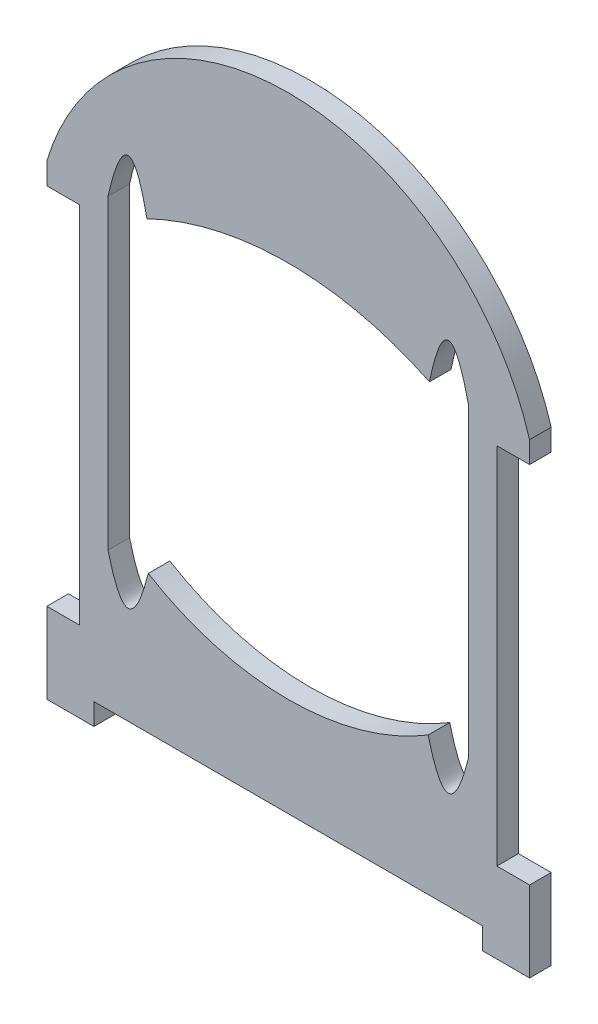
SolidWorks part; units mm, degrees
ref_plane "Front Plane" through (0, 0, 0) normal (0, 0, 1) x (1, 0, 0)
ref_plane "Top Plane" through (0, 0, 0) normal (0, 1, 0) x (1, 0, 0)
ref_plane "Right Plane" through (0, 0, 0) normal (1, 0, 0) x (0, 0, -1)
sketch "Sketch1" plane through (0, 0, 0) normal (0, 0, 1) x (1, 0, 0)
  line L0 (-31.0002, 89.8) -> (31.0002, 89.8) construction
  line L1 (-19.45, 0) -> (-19.45, 22.2)
  line L2 (-19.45, 22.2) -> (19.45, 22.2) construction
  line L3 (19.45, 3) -> (19.45, 22.2)
  line L4 (19.45, 22.2) -> (25.05, 22.2) construction
  line L5 (22.25, 22.2) -> (22.25, 16.6) construction
  line L6 (25.05, 22.2) -> (25.05, 71.1)
  line L7 (29, 72.2) -> (29, -3)
  line L8 (22.25, 16.6) -> (22.25, 71.1) construction
  line L9 (19.6329, 71.1) -> (19.6329, 64.8)
  line L10 (-22.25, 16.6) -> (-22.25, 71.1) construction
  line L11 (-22.25, 22.2) -> (-22.25, 16.6) construction
  line L12 (-19.45, 22.2) -> (-25.05, 22.2) construction
  line L13 (-19.6329, 71.1) -> (-19.6329, 64.8)
  line L14 (-29, 72.2) -> (-29, 0)
  line L15 (-25.05, 22.2) -> (-25.05, 71.1)
  line L16 (-19.45, 0) -> (-19.45, 22.2)
  line L18 (0, 89.8) -> (0, 69.3) construction
  line L19 (25.05, 64.8) -> (33.55, 64.8)
  line L20 (-25.05, 64.8) -> (-33.55, 64.8)
  line L21 (33.55, 64.8) -> (33.55, 61.8)
  line L22 (33.55, 61.8) -> (29, 61.8)
  line L23 (-30.35, 3) -> (29, 3)
  line L24 (-33.55, 0) -> (33.55, 0)
  line L25 (-33.55, 0) -> (-33.55, 11.2)
  line L26 (-33.55, 11.2) -> (-29, 11.2)
  line L27 (33.55, 11.2) -> (29, 11.2)
  line L28 (33.55, 0) -> (33.55, 11.2)
  line L29 (-33.55, 64.8) -> (-33.55, 61.8)
  line L30 (-33.55, 61.8) -> (-29, 61.8)
  arc A0 (-19.45, 22.2) -> (19.45, 22.2) centre (0, 54.1817) ccw
  arc A1 (-19.6329, 64.8) -> (19.6329, 64.8) centre (0, 24.222) cw
  arc A2 (-33.55, 64.8) -> (33.55, 64.8) centre (0, 54.7879) cw
  spline S0 degree 2 poles (19.45, 22.2) (22.25, 11) (25.05, 22.2) knots 0 0 0 1 1 1
  spline S1 degree 2 poles (19.6329, 64.8) (22.1871, 77.4003) (25.05, 64.8) knots 0 0 0 1 1 1
  spline S2 degree 2 poles (-19.6329, 64.8) (-22.1871, 77.4003) (-25.05, 64.8) knots 0 0 0 1 1 1
  spline S3 degree 2 poles (-19.45, 22.2) (-22.25, 11) (-25.05, 22.2) knots 0 0 0 1 1 1
  point P8 (0, 22.2)
  point P37 (0, 89.8)
  point P47 (-0.675, 3)
  point P50 (0, 0)
  point P56 (0, 89.8)
  dimension "D2" = 22.2
  dimension "D3" = 38.9
  dimension "D4" = 5.6
  dimension "D5" = 5.6
  dimension "D6" = 5.4171
  dimension "D7" = 29
  dimension "D8" = 29
  dimension "D9" = 6.3
  dimension "D10" = 0
  dimension "D11" = 6.3
  dimension "D13" = 20.5
  dimension "D14" = 8.5
  dimension "D15" = 8.5
  dimension "D16" = 89.8
  dimension "D17" = 3
  dimension "D18" = 11.2
sketch "Sketch2" plane through (0, 0, 0) normal (0, 0, 1) x (1, 0, 0)
  line L0 (-33.55, 0) -> (33.55, 0)
  line L1 (33.55, 0) -> (33.55, 11.2)
  line L2 (33.55, 11.2) -> (29, 11.2)
  line L3 (29, 11.2) -> (29, 61.8)
  line L4 (29, 61.8) -> (33.55, 61.8)
  line L5 (33.55, 61.8) -> (33.55, 64.8)
  line L6 (-33.55, 0) -> (-33.55, 11.2)
  line L7 (-33.55, 11.2) -> (-29, 11.2)
  line L8 (-29, 11.2) -> (-29, 61.8)
  line L9 (-29, 61.8) -> (-33.55, 61.8)
  line L10 (-33.55, 61.8) -> (-33.55, 64.8)
  line L11 (-25.05, 64.8) -> (-25.05, 22.2)
  line L12 (25.05, 22.2) -> (25.05, 64.8)
  arc A0 (-33.55, 64.8) -> (33.55, 64.8) centre (0, 54.7879) cw
  arc A1 (19.6329, 64.8) -> (-19.6329, 64.8) centre (0, 24.222) ccw
  arc A2 (-19.45, 22.2) -> (19.45, 22.2) centre (0, 54.1817) ccw
  spline S0 degree 2 poles (-25.05, 64.8) (-22.1871, 77.4003) (-19.6329, 64.8) knots 0 0 0 1 1 1
  spline S1 degree 2 poles (19.6329, 64.8) (22.1871, 77.4003) (25.05, 64.8) knots 0 0 0 1 1 1
  spline S2 degree 2 poles (-25.05, 22.2) (-22.25, 11) (-19.45, 22.2) knots 0 0 0 1 1 1
  spline S3 degree 2 poles (19.45, 22.2) (22.25, 11) (25.05, 22.2) knots 0 0 0 1 1 1
  point P5 (0, 0)
extrude "Boss-Extrude1" add sketch "Sketch2" along normal blind 3
sketch "Sketch4" plane through (0, 0, 3) normal (0, 0, 1) x (1, 0, 0)
  line L0 (-27, 0) -> (27, 0)
  line L1 (-33.55, 0) -> (33.55, 0) construction
  line L2 (-27, 0) -> (-27, 3)
  line L3 (-30.35, 3) -> (29, 3) construction
  line L4 (-27, 3) -> (27, 3)
  line L5 (27, 3) -> (27, 0)
  point P6 (0, 0)
  dimension "D1" = 54
extrude "Cut-Extrude1" cut sketch "Sketch4" against normal blind 10
